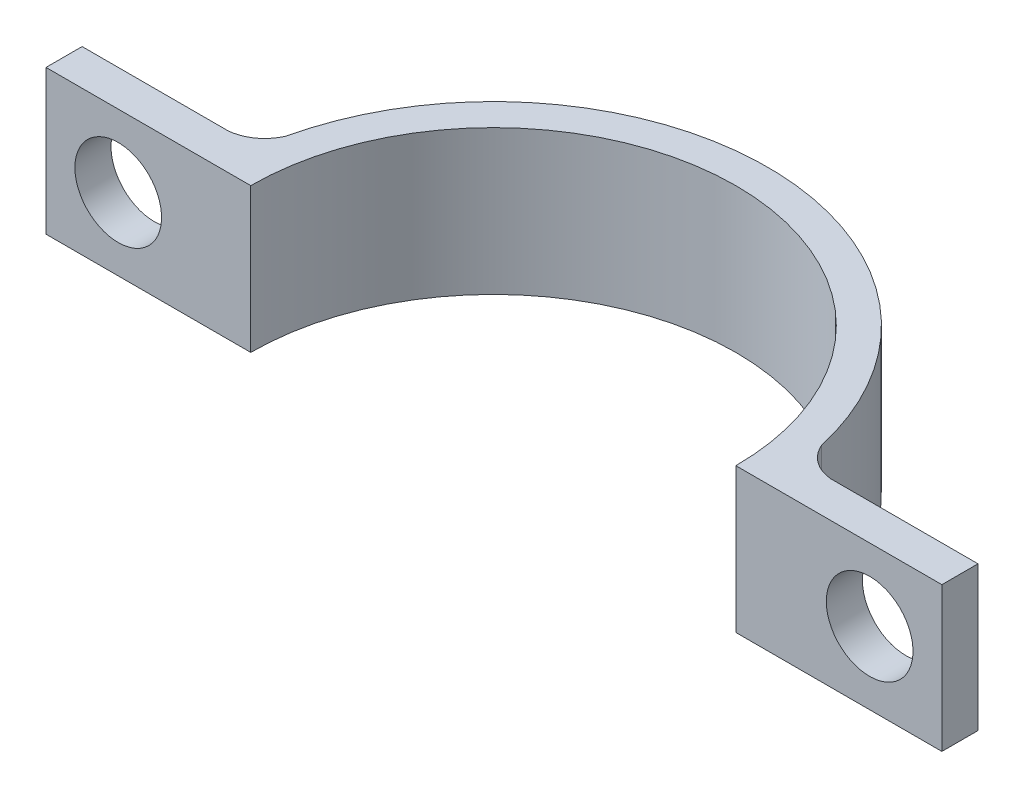
SolidWorks part; units mm, degrees
material "6061 Alloy"
ref_plane "Front Plane" through (0, 0, 0) normal (0, 0, 1) x (1, 0, 0)
ref_plane "Top Plane" through (0, 0, 0) normal (0, 1, 0) x (1, 0, 0)
ref_plane "Right Plane" through (0, 0, 0) normal (1, 0, 0) x (0, 0, -1)
sketch "Sketch1" plane through (0, 0, 0) normal (0, 1, 0) x (1, 0, 0)
  line L0 (-14.9927, -10.0527) -> (-29.1654, -10.0527)
  line L1 (18.5873, -10.0527) -> (32.8499, -10.0527)
  line L2 (-19.0446, -7.5527) -> (-29.1654, -7.5527)
  line L3 (22.6392, -7.5527) -> (32.8499, -7.5527)
  line L4 (-29.1654, -7.5527) -> (-29.1654, -10.0527)
  line L5 (32.8499, -7.5527) -> (32.8499, -10.0527)
  line L6 (1.7973, 6.9473) -> (1.7973, -10.0527) construction
  arc A1 (20.3265, -5.8491) -> (-16.7319, -5.8491) centre (1.7973, -10.0527) ccw
  arc A2 (22.6392, -7.5527) -> (20.3265, -5.8491) centre (22.9029, -4.773) cw
  arc A3 (-19.0446, -7.5527) -> (-16.7319, -5.8491) centre (-19.3084, -4.773) ccw
  arc A4 (18.5873, -10.0527) -> (-14.9927, -10.0527) centre (1.7973, -10.0527) ccw
extrude "Boss-Extrude1" add sketch "Sketch1" along normal blind 10
sketch "Sketch2" plane through (0, 0, 7.5527) normal (0, 0, -1) x (-1, 0, 0)
  line L0 (-32.8499, 0) -> (-32.8499, 5) construction
  line L1 (-32.8499, 10) -> (-32.8499, 0) construction
  line L2 (-32.8499, 5) -> (-27.8499, 5) construction
  line L3 (29.1654, 5) -> (24.1654, 5) construction
  line L4 (29.1654, 10) -> (29.1654, 0) construction
  circle A0 centre (24.1654, 5) radius 3
  circle A1 centre (-27.8499, 5) radius 3
extrude "Cut-Extrude1" cut sketch "Sketch2" against normal blind 8
